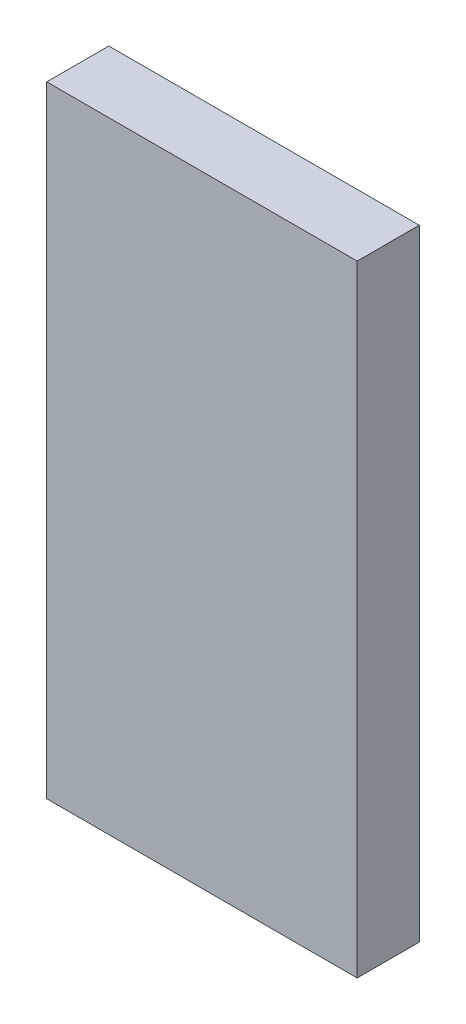
SolidWorks part; units mm, degrees
ref_plane "Front Plane" through (0, 0, 0) normal (0, 0, 1) x (1, 0, 0)
ref_plane "Top Plane" through (0, 0, 0) normal (0, 1, 0) x (1, 0, 0)
ref_plane "Right Plane" through (0, 0, 0) normal (1, 0, 0) x (0, 0, -1)
sketch "Sketch1" plane through (0, 0, 0) normal (0, 0, 1) x (1, 0, 0)
  line L1 (30, -60) -> (-30, -60)
  line L2 (30, -60) -> (30, 60)
  line L3 (30, 60) -> (-30, 60)
  line L4 (-30, -60) -> (-30, 60)
  line L5 (30, -60) -> (-30, 60) construction
  line L6 (30, 60) -> (-30, -60) construction
  point P0 (0, 0)
  dimension "D1" = 60
  dimension "D2" = 120
extrude "Boss-Extrude1" add sketch "Sketch1" along normal blind 12
